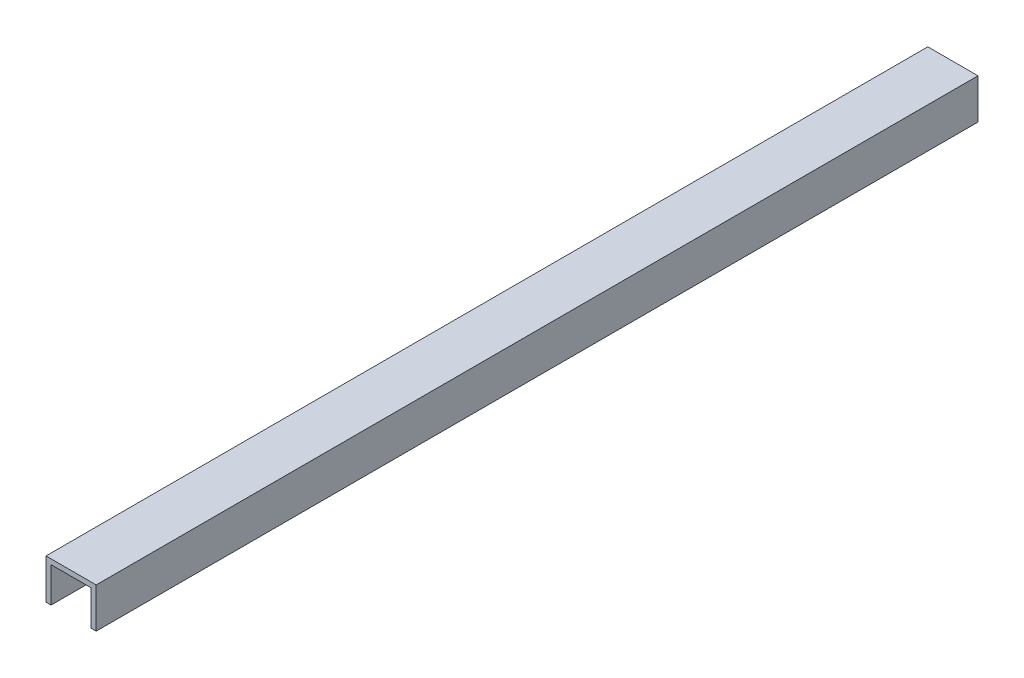
SolidWorks part; units mm, degrees
ref_plane "Front Plane" through (0, 0, 0) normal (0, 0, 1) x (1, 0, 0)
ref_plane "Top Plane" through (0, 0, 0) normal (0, 1, 0) x (1, 0, 0)
ref_plane "Right Plane" through (0, 0, 0) normal (1, 0, 0) x (0, 0, -1)
sketch "Sketch1" plane through (0, 0, 0) normal (0, 0, 1) x (1, 0, 0)
  line L0 (14.3002, 0) -> (15.9004, 0)
  line L1 (0, 0) -> (1.6002, 0)
  line L2 (0, 0) -> (0, 12.7)
  line L3 (0, 12.7) -> (15.9004, 12.7)
  line L4 (15.9004, 0) -> (15.9004, 12.7)
  line L6 (1.6002, 0) -> (1.6002, 11.0998)
  line L7 (1.6002, 11.0998) -> (14.3002, 11.0998)
  line L8 (14.3002, 0) -> (14.3002, 11.0998)
  dimension "D1" = 12.7
  dimension "D2" = 12.7
  dimension "D3" = 1.6002
  dimension "D4" = 1.6002
extrude "Boss-Extrude1" add sketch "Sketch1" against normal blind 279.4
